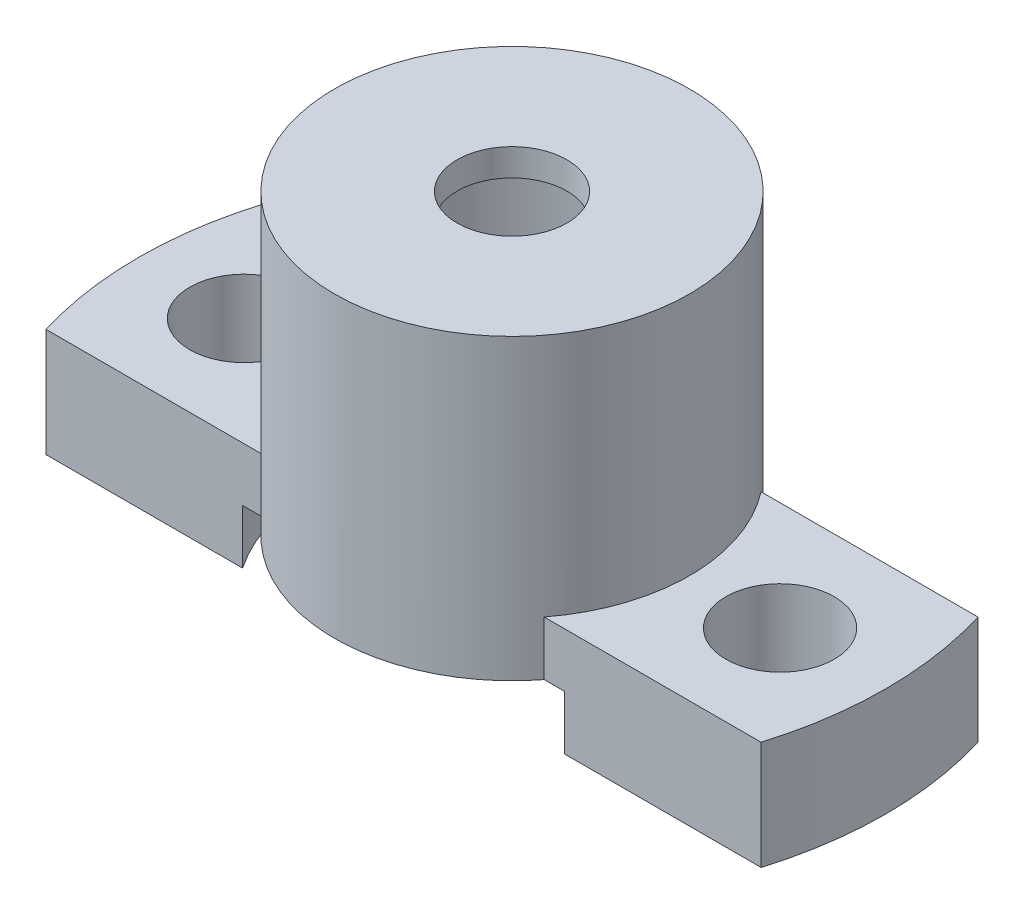
SolidWorks part; units mm, degrees
ref_plane "Front Plane" through (0, 0, 0) normal (0, 0, 1) x (1, 0, 0)
ref_plane "Top Plane" through (0, 0, 0) normal (0, 1, 0) x (1, 0, 0)
ref_plane "Right Plane" through (0, 0, 0) normal (1, 0, 0) x (0, 0, -1)
sketch "..." plane through (0, 0, 0) normal (0, 1, 0) x (1, 0, 0)
  circle A0 centre (0, 0) radius 5.55
  circle A1 centre (0, 0) radius 6.55
  dimension "D2" = 11.1
  dimension "D1" = 1
sketch "Sketch5" plane through (0, 0, 0) normal (0, 1, 0) x (-1, 0, 0)
  circle A0 centre (0, 0) radius 6.55
  circle A1 centre (0, 0) radius 2.025
  dimension "D1" = 4.05
  dimension "D2" = 13.1
extrude "Ext_TopMagnetRoom" add sketch "Sketch5" along normal blind 1
sketch "Sketch7" plane through (0, 0, 0) normal (0, -1, 0) x (1, 0, 0)
  circle A0 centre (0, 0) radius 5.05
  circle A1 centre (0, 0) radius 6.55
  circle A3 centre (0, 0) radius 6.55 construction
  dimension "D1" = 10.1
extrude "Ext_MagnetRoom" add sketch "Sketch7" along normal blind 4
sketch "Sketch6" plane through (0, -4, 0) normal (0, -1, 0) x (1, 0, 0)
  line L0 (13.1868, -4) -> (5.1868, -4)
  line L1 (-13.1868, -4) -> (-5.1868, -4)
  line L2 (-13.1868, 4) -> (-5.1868, 4)
  line L3 (5.1868, 4) -> (13.1868, 4)
  line L4 (13.7801, 0) -> (6.55, 0) construction
  line L5 (6.55, 0) -> (0, 0) construction
  line L6 (0, 0) -> (-6.55, 0) construction
  line L7 (-6.55, 0) -> (-13.7801, 0) construction
  line L10 (13.1868, -4) -> (13.1868, 4) construction
  arc A0 (13.1868, 4) -> (13.1868, -4) centre (0, 0) cw
  arc A1 (-13.1868, -4) -> (-13.1868, 4) centre (0, 0) cw
  arc A2 (5.1868, -4) -> (5.1868, 4) centre (0, 0) ccw
  arc A3 (-5.1868, -4) -> (-5.1868, 4) centre (0, 0) cw
  circle A4 centre (0, 0) radius 6.55 construction
extrude "Bottom-arms fixing with support" add sketch "Sketch6" against normal blind 2
sketch "Sketch9" plane through (0, -4, 0) normal (0, -1, 0) x (1, 0, 0)
  line L0 (13.1868, 4) -> (5.9368, 4)
  line L1 (13.1868, 4) -> (5.1868, 4) construction
  line L2 (-13.1868, -4) -> (-5.9368, -4)
  line L3 (-13.1868, -4) -> (-5.1868, -4) construction
  line L4 (-13.1868, 4) -> (-5.9368, 4)
  line L5 (13.1868, -4) -> (5.9368, -4)
  line L6 (-5.1868, 4) -> (-13.1868, 4) construction
  line L7 (5.1868, -4) -> (13.1868, -4) construction
  line L8 (-5.9368, 4) -> (-5.1868, 4) construction
  arc A1 (-13.1868, -4) -> (-13.1868, 4) centre (0, 0) cw
  arc A2 (13.1868, 4) -> (13.1868, -4) centre (0, 0) cw
  arc A3 (-5.9368, -4) -> (-5.9368, 4) centre (0, 0) cw
  arc A4 (5.9368, 4) -> (5.9368, -4) centre (0, 0) cw
  circle A5 centre (0, 0) radius 6.55 construction
  dimension "D1" = 0.75
extrude "Bottom- Fixing arms End" add sketch "Sketch9" along normal blind 2
sketch "Esquisse1" plane through (0, -2, 0) normal (0, 1, 0) x (1, 0, 0)
  circle A0 centre (-9.8868, 0) radius 2
  circle A1 centre (9.8868, 0) radius 2
  circle A4 centre (-9.8868, 0) radius 2.25 construction
  circle A5 centre (9.8868, 0) radius 2.25 construction
  dimension "D1" = 4
extrude "Ext_HoleMounted" cut sketch "Esquisse1" against normal through all
sketch "Sketch10" plane through (0, 1, 0) normal (0, 1, 0) x (1, 0, 0)
  circle A0 centre (0, 0) radius 5.05
  circle A1 centre (0, 0) radius 6.55
  circle A3 centre (0, 0) radius 5.05 construction
  circle A4 centre (0, 0) radius 6.55 construction
extrude "chamber" add sketch "Sketch10" along normal blind 5
sketch "Sketch11" plane through (0, 6, 0) normal (0, 1, 0) x (1, 0, 0)
  circle A0 centre (0, 0) radius 6.55
  circle A1 centre (0, 0) radius 2.025
  circle A3 centre (0, 0) radius 6.55 construction
  circle A6 centre (0, 0) radius 2.025 construction
extrude "Boss-Extrude4" add sketch "Sketch11" along normal blind 1
sketch "Esquisse2" [suppressed] plane through (0, 0, 0) normal (0, 0, 1) x (1, 0, 0)
  line L1 (26.7806, 17.3131) -> (-24.7319, 17.3131)
  line L2 (26.7806, 17.3131) -> (26.7806, -15.9722)
  line L3 (26.7806, -15.9722) -> (-24.7319, -15.9722)
  line L4 (-24.7319, 17.3131) -> (-24.7319, -15.9722)
extrude "Enlèv. mat.-Extru.1" [suppressed] cut sketch "Esquisse2" along normal through all
sketch "Sketch12" plane through (0, -6, 0) normal (0, -1, 0) x (1, 0, 0)
  circle A0 centre (-9.8868, 0) radius 2.5
  circle A1 centre (9.8868, 0) radius 2.5
  dimension "D1" = 5
  dimension "D2" = 5
extrude "Cut-Extrude1" [suppressed] cut sketch "Sketch12" against normal blind 10
sketch "Sketch13" plane through (0, -4, 0) normal (0, -1, 0) x (1, 0, 0)
  circle A0 centre (0, 0) radius 5.2
  dimension "D1" = 10.4
extrude "Cut-Extrude2" cut sketch "Sketch13" against normal up to surface (4 mm away) up to face at (0, 0, 2.025)
equation "\"magnet_DI\"= 3mm'inner diameter of the o-ring magnet"
equation "\"magnet_DE\"= 8mm'external diameter of the o-ring magnet"
equation "\"magnet_H\"= 3mm'tall of the magnet"
equation "\"magnet_levitation_DI\"= 0mm'inner diameter of the o-ring magnet"
equation "\"magnet_levitation_DE\"= 1mm'external diameter of the o-ring magnet"
equation "\"magnet_levitation_H\"= 0.5mm'tall of the magnet"
equation "\"gap_magnet_H\"= 1mm'gap between the 2 magnets"
equation "\"plug_DI\"= 1.5mm'size of the inner extrude of the plug (finger contact)"
equation "\"coil_H\"= 8mm 'height coil"
equation "\"coil_W\"= 0.2mm 'width coil"
equation "\"mandrine_freegap\"= 0.2mm 'gap between the magnet and the mandrine. "
equation "\"mandrine_bottom_H\"= 0.5mm 'border of the bottom of the mandrine"
equation "\"mandrine_coilmagnet_wall\"= 0.15mm"
equation "\"mandrine_magnet_lev\"= 3mm' gap needed for the levitation of the rod"
equation "\"mandrine_border_H\"= 2mm 'border of the top of the mandrine"
equation "\"mandrine_epoxy_W\"= 0.5mm 'width epoxy"
equation "\"mandrine_DI\"= \"mandrine_freegap\"*2+\"magnet_DE\""
equation "\"mandrine_DE\"= (\"mandrine_epoxy_W\"+\"coil_W\"+\"mandrine_coilmagnet_wall\")*2+\"mandrine_DI\""
equation "\"mandrine_H\"= \"magnet_levitation_H\"+\"mandrine_magnet_lev\"+\"magnet_H\"+\"gap_magnet_H\"/2+\"coil_H\"/2+\"mandrine_border_H\""
equation "\"mandrine_hat_W\"= 1mm"
equation "\"tower_freegap\"= 1mm 'gap between the actuator and the tower"
equation "\"tower_DI\"= \"mandrine_DE\"+\"tower_freegap\""
equation "\"tower_W\"= 1mm'width of the tower"
equation "\"tower_link_H\"= 2mm"
equation "\"tower_link_W\"= 4mm"
equation "\"tower_channel_W\"= 1mm"
equation "\"tower_renforcement_H\"= 2mm"
equation "\"apex_tower_Dbase\"= 2.5mm 'diameter of the holes in order to curve"
equation "\"apex_tower_Rbase1\"= 0.75mm 'diameter of the holes in order to curve"
equation "\"apex_tower_Rbase2\"= 1mm 'diameter of the holes in order to curve"
equation "\"apex_tower_Rbase3\"= 1.25mm 'diameter of the holes in order to curve"
equation "\"apex_tower_holeOpening1\"= \"apex_tower_Rbase1\"*7/8"
equation "\"apex_tower_holeOpening2\"= \"apex_tower_Rbase2\"*7/8"
equation "\"apex_tower_holeOpening3\"= \"apex_tower_Rbase3\"*7/8"
equation "\"apex_tower_Hbase\"= 1mm 'gap between the bottom of the tower and the holes"
equation "\"apex_tower_hole\"= 4.5mm 'witdh of the hole"
equation "\"apex_tower_H\"= 0mm '\"mandrine_H\"-\"tower_link_H\""
equation "\"apex_tower_H2\"= \"apex_tower_H\"+7mm"
equation "\"actuator1.x\"= 42.59mm"
equation "\"actuator2.x\"= 80.026mm"
equation "\"actuator3.x\"= 0mm"
equation "\"actuator4.x\"= 14.55mm"
equation "\"actuator5.x\"= 14.557mm"
equation "\"actuator6.x\"= 12.497mm"
equation "\"actuator7.x\"= 27.494mm"
equation "\"actuator8.x\"= 39.75mm"
equation "\"actuator9.x\"= 41.5767mm"
equation "\"actuator10.x\"= 41.148mm"
equation "\"actuator11.x\"= 70.869mm"
equation "\"actuator12.x\"= 77.15mm"
equation "\"actuator13.x\"= 70.87mm"
equation "\"actuator14.x\"= 80.15mm"
equation "\"actuator15.x\"= 92.21mm"
equation "\"actuator16.x\"= 97.61mm"
equation "\"actuator17.x\"= 87.41mm"
equation "\"actuator18.x\"= 109.08mm"
equation "\"actuator19.x\"= 125.04mm"
equation "\"actuator20.x\"= 119.466mm"
equation "\"actuator21.x\"= 115.558mm"
equation "\"actuator22.x\"= 142.74mm"
equation "\"actuator23.x\"= 145.93mm"
equation "\"actuator24.x\"= 131.11mm"
equation "\"actuator1.y\"= 101.167mm"
equation "\"actuator2.y\"= 120.647mm"
equation "\"actuator3.y\"= 45.677mm"
equation "\"actuator4.y\"= 66.047mm"
equation "\"actuator5.y\"= 45.327mm"
equation "\"actuator6.y\"= 28.807mm"
equation "\"actuator7.y\"= 13.807mm"
equation "\"actuator8.y\"= 30.087mm"
equation "\"actuator9.y\"= 49.157mm"
equation "\"actuator10.y\"= 71.787mm"
equation "\"actuator11.y\"= 78.407mm"
equation "\"actuator12.y\"= 52.377mm"
equation "\"actuator13.y\"= 25.793mm"
equation "\"actuator14.y\"= 0.711mm"
equation "\"actuator15.y\"= 34.092mm"
equation "\"actuator16.y\"= 57.427mm"
equation "\"actuator17.y\"= 86.987mm"
equation "\"actuator18.y\"= 92.077mm"
equation "\"actuator19.y\"= 63.187mm"
equation "\"actuator20.y\"= 34.434mm"
equation "\"actuator21.y\"= 0mm"
equation "\"actuator22.y\"= 38.901mm"
equation "\"actuator23.y\"= 70.278mm"
equation "\"actuator24.y\"= 100.8741mm"
equation "\"actuator1.z\"= 45.834mm"
equation "\"actuator2.z\"= 37.834mm"
equation "\"actuator3.z\"= 13mm"
equation "\"actuator4.z\"= 33.9226mm"
equation "\"actuator5.z\"= 51.234mm"
equation "\"actuator6.z\"= 29.9773mm"
equation "\"actuator7.z\"= 49.434mm"
equation "\"actuator8.z\"= 31.7209mm"
equation "\"actuator9.z\"= 60.084mm"
equation "\"actuator10.z\"= 45.3632mm"
equation "\"actuator11.z\"= 42.0948mm"
equation "\"actuator12.z\"= 33.6927mm"
equation "\"actuator13.z\"= 48.7255mm"
equation "\"actuator14.z\"= 45.0141mm"
equation "\"actuator15.z\"= 63.034mm"
equation "\"actuator16.z\"= 50.5713mm"
equation "\"actuator17.z\"= 61.634mm"
equation "\"actuator18.z\"= 46.3531mm"
equation "\"actuator19.z\"= 57.834mm"
equation "\"actuator20.z\"= 58.534mm"
equation "\"actuator21.z\"= 44.984mm"
equation "\"actuator22.z\"= 45.5969mm"
equation "\"actuator23.z\"= 42.2671mm"
equation "\"actuator24.z\"= 33.4578mm"
equation "\"shape_freegap\"= \"tower_freegap\""
equation "\"shape_strip_witdh\"= 5mm"
equation "\"shape_holes_sweat_D\"= 2mm"
equation "\"shape_holes_actuator_D\"= \"magnet_DE\"+\"shape_freegap\"+1mm"
equation "\"shape_holes_actuator_extD\"= \"shape_holes_actuator_D\"+2*\"shape_strip_witdh\""
equation "\"shape_holes_wet_D\"= 2mm"
equation "\"amortisseur_Dext\"= 18mm"
equation "\"amortisseur_Din\"= 7mm"
equation "\"amortisseur_H\"= 20mm"
equation "\"amortisseur_prise_D\"= 10mm"
equation "\"amortisseur_bourlet_H\"= 0.5mm"
equation "\"fixation_prise_base_D\"= (\"amortisseur_prise_D\"+3)"
equation "\"fixation_prise_base_H\"= 1mm"
equation "\"fixation_prise_tete_D\"= (\"amortisseur_Dext\"+3)"
equation "\"fixation_prise_tete_H\"= 2.5mm"
equation "\"fixation_D\"= \"fixation_prise_tete_D\" + 2mm"
equation "\"fixation_H\"= \"fixation_prise_base_H\" + \"fixation_prise_tete_H\" + 3mm"
equation "\"fixation_zone_accroche_D\"= 3*\"fixation_D\""
equation "\"oring_R\"= 0.75mm"
equation "\"oring_R1\"= 0.25mm"
equation "\"oring_R2\"= 0.3mm"
equation "\"oring_R3\"= 0.75mm"
equation "\"guide_H1\"=4mm"
equation "\"guide_H2\"=1mm"
equation "\"guide_W1\"=1mm"
equation "\"guide_openAngle\"=360deg"
equation "\"guide_ecrou_DI\"=5mm"
equation "\"guide_ecrou_DE\"=8mm"
equation "\"guide_vis_DI\"=4mm"
equation "\"guide_rondelle_DE\"=9mm"
equation "\"D1@...\" = \"guide_W1\""
equation "\"D2@...\" = \"tower_DI\""
equation "\"D2@Sketch5\"=\"tower_DI\"+\"tower_W\"*2"
equation "\"D1@Sketch5\"=\"magnet_DI\"+1.05"
equation "\"D1@Ext_TopMagnetRoom\" = \"guide_W1\""
equation "\"D1@Ext_MagnetRoom\" = \"guide_H1\""
equation "\"D1@Sketch7\"=\"mandrine_DE\""
